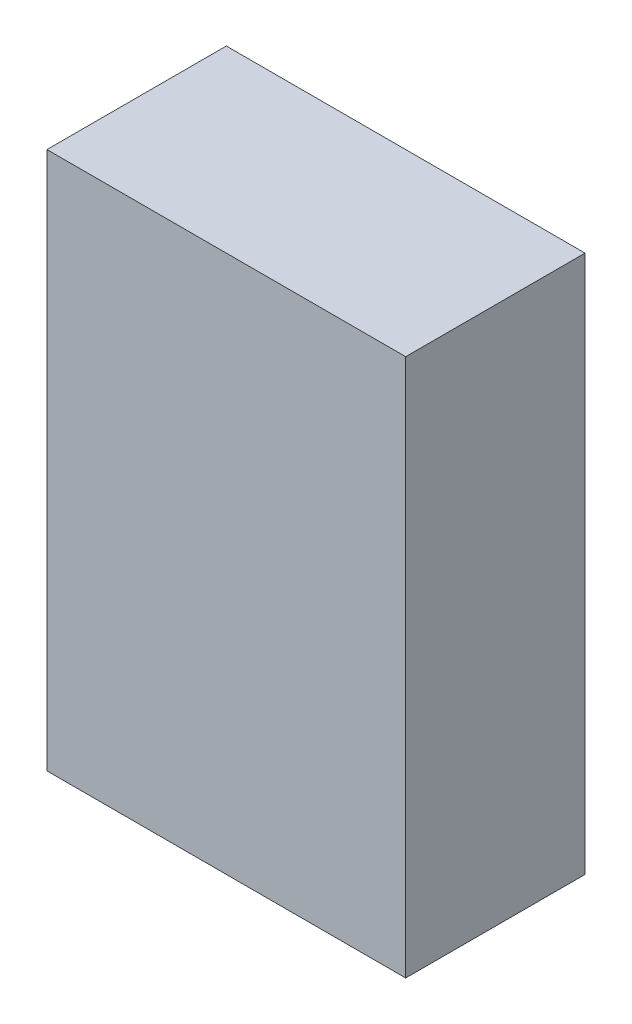
SolidWorks part; units mm, degrees
material "Chrome Stainless Steel"
ref_plane "Front Plane" through (0, 0, 0) normal (0, 0, 1) x (1, 0, 0)
ref_plane "Top Plane" through (0, 0, 0) normal (0, 1, 0) x (1, 0, 0)
ref_plane "Right Plane" through (0, 0, 0) normal (1, 0, 0) x (0, 0, -1)
sketch "Sketch1" plane through (0, 0, 0) normal (0, 0, 1) x (1, 0, 0)
  line L1 (-2, 3) -> (2, 3)
  line L2 (-2, 3) -> (-2, -3)
  line L3 (-2, -3) -> (2, -3)
  line L4 (2, 3) -> (2, -3)
  line L5 (0, -3) -> (0, 3) construction
  line L6 (-2, 0) -> (2, 0) construction
  point P0 (0, 0)
  dimension "D1" = 4
  dimension "D2" = 6
extrude "Boss-Extrude1" add sketch "Sketch1" along normal blind 2
